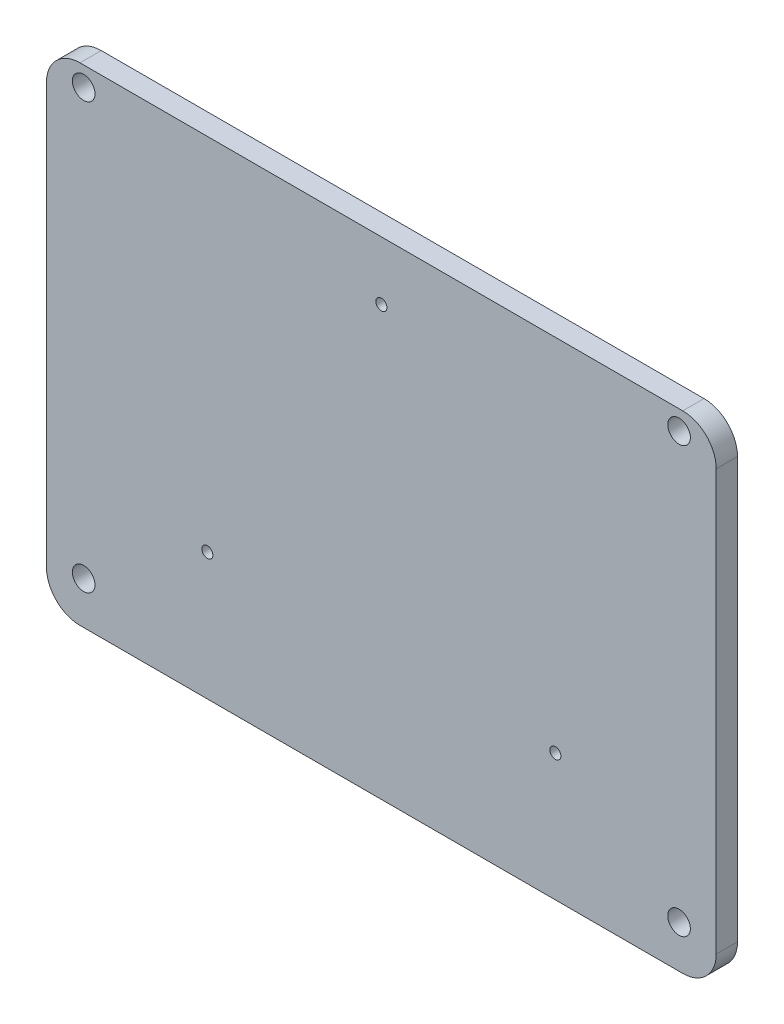
SolidWorks part; units mm, degrees
ref_plane "Front Plane" through (0, 0, 0) normal (0, 0, 1) x (1, 0, 0)
ref_plane "Top Plane" through (0, 0, 0) normal (0, 1, 0) x (1, 0, 0)
ref_plane "Right Plane" through (0, 0, 0) normal (1, 0, 0) x (0, 0, -1)
sketch "Sketch1" plane through (0, 0, 0) normal (0, 0, 1) x (1, 0, 0)
  line L0 (0, 0) -> (-51.9615, -30) construction
  line L1 (51.9615, -30) -> (0, 0) construction
  line L2 (0, 0) -> (0, 60) construction
  line L4 (-100, 77.5) -> (100, 77.5)
  line L5 (-100, 77.5) -> (-100, -77.5)
  line L6 (-100, -77.5) -> (100, -77.5)
  line L7 (100, 77.5) -> (100, -77.5)
  line L8 (0, -77.5) -> (0, 77.5) construction
  line L9 (-100, 0) -> (100, 0) construction
  line L14 (-88.9, 71.7) -> (88.9, 71.7) construction
  line L15 (-88.9, 71.7) -> (-88.9, -55.3) construction
  line L16 (-88.9, -55.3) -> (88.9, -55.3) construction
  line L17 (88.9, 71.7) -> (88.9, -55.3) construction
  circle A4 centre (0, 0) radius 23.7932 construction
  circle A6 centre (0, 0) radius 68 construction
  circle A7 centre (-88.9, 71.7) radius 3.38
  circle A8 centre (88.9, 71.7) radius 3.38
  circle A9 centre (88.9, -55.3) radius 3.38
  circle A10 centre (-88.9, -55.3) radius 3.38
  point P2 (0, 71.7)
  point P4 (0, 60)
  point P5 (-88.9, 60)
  point P7 (51.9615, -30)
  point P8 (-51.9615, -30)
  dimension "D4" = 136
  dimension "D2" = 47.5864
  dimension "D6" = 6.76
  dimension "D5" = 60
  dimension "D3" = 120
  dimension "D1" = 120
  dimension "D7" = 177.8
  dimension "D8" = 127
  dimension "D9" = 200
  dimension "D10" = 155
  dimension "D11" = 22.2
extrude "Boss-Extrude1" add sketch "Sketch1" along normal blind 6.35
hole_wizard "M4x0.7 Tapped Hole1" positions "3DSketch2" profile "Sketch3" tap size "M4x0.7" standard "ANSI Metric" end condition through all
sketch3d "3DSketch2"
  point P0 (51.9615, -30, 0)
  point P3 (-51.9615, -30, 0)
  point P10 (0, 60, 0)
  point P14 (0, 0, 0)
  point P15 (0, 0, 0)
sketch "Sketch3" plane through (51.9615, -30, 0) normal (1, 0, 0) x (0, 1, 0)
  line L0 (0, 0) -> (0, 6.35)
  line L1 (0, 6.35) -> (1.65, 6.35)
  line L2 (1.65, 6.35) -> (1.65, 0)
  line L5 (1.65, 0) -> (0, 0)
  line L11 (0, -6.35) -> (0, 107.95) construction
  dimension "Thru Tap Drill Dia." = 3.3
  dimension "Thru Tap Drill Depth" = 6.35
cosmetic thread "Hole Thread1" parameters "D2"=4
cosmetic thread "Hole Thread2" parameters "D2"=4
cosmetic thread "Hole Thread3" parameters "D2"=4
sketch "Sketch4" plane through (0, 0, 6.35) normal (0, 0, 1) x (1, 0, 0)
  line L0 (100, 77.5) -> (100, -77.5) construction
  line L1 (-100, -77.5) -> (100, -77.5)
  line L2 (-100, -77.5) -> (-100, -68)
  line L3 (-100, -68) -> (100, -68)
  line L4 (100, -77.5) -> (100, -68)
  point P7 (100, -67.0463)
  dimension "D1" = 9.5
extrude "Cut-Extrude1" cut sketch "Sketch4" against normal through all both and the other way through all
fillet "Fillet1" radius 10 4 edges at (100, -68, 3.175) (100, 77.5, 3.175) (-100, 77.5, 3.175) (-100, -68, 3.175)
equation "\"D1@Sketch1\"=\"D3@Sketch1\""
equation "\"D11@Sketch1\"=20.00mm+1.94600+0.25400"
